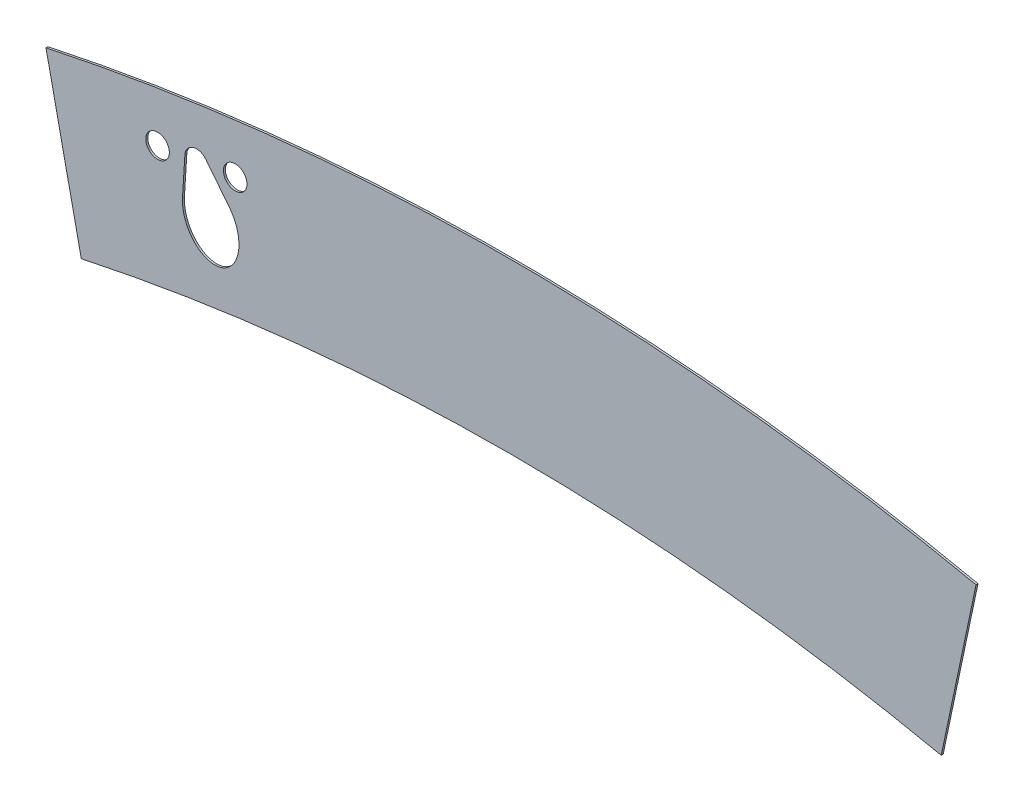
SolidWorks part; units mm, degrees
material "6061 Alloy"
ref_plane "front" through (0, 0, 0) normal (0, 0, 1) x (1, 0, 0)
ref_plane "top" through (0, 0, 0) normal (0, 1, 0) x (1, 0, 0)
ref_plane "right" through (0, 0, 0) normal (1, 0, 0) x (0, 0, -1)
sketch "Sketch1" plane through (0, 0, 0) normal (0, 0, 1) x (1, 0, 0)
  line L0 (0, 0) -> (0, -273.05) construction
  line L1 (0, 0) -> (383.281, 0) construction
  line L2 (-752.475, -79.7743) -> (-695.3504, -346.782)
  line L3 (752.475, -79.7743) -> (696.1124, -346.9455)
  line L4 (-533.4, -39.8611) -> (-450.8253, -303.8415) construction
  line L5 (-527.7688, -117.4654) -> (-531.605, -179.2171)
  line L6 (-493.8044, -106.8411) -> (-455.4626, -155.3993)
  arc A0 (752.475, -79.7743) -> (-752.475, -79.7743) centre (0, -3588.766) ccw
  arc A1 (696.1124, -346.9455) -> (-695.3504, -346.782) centre (0, -3588.766) ccw
  circle A2 centre (-446.3034, -108.204) radius 19.05
  arc A3 (-493.8044, -106.8411) -> (-527.7688, -117.4654) centre (-508.7554, -118.6466) ccw
  circle A4 centre (-571.9318, -126.7714) radius 19.05
  ellipse E0 centre (-486.0066, -191.3716) end of major axis (-503.0682, -136.8278) minor radius 44.45 (-531.605, -179.2171) -> (-455.4626, -155.3993) ccw
  dimension "D1" = 3588.766
  dimension "D5" = 17.37
  dimension "D7" = 38.1
  dimension "D12" = 19.05
  dimension "D2" = 1504.95
  dimension "D3" = 273.05
  dimension "D4" = 695.3504
  dimension "D6" = 533.4
  dimension "D8" = 158.75
  dimension "D9" = 88.9
  dimension "D10" = 57.15
  dimension "D11" = 752.475
  dimension "D13" = 696.1124
  dimension "D14" = 82.55
  dimension "D15" = 446.3034
  dimension "D16" = 108.204
  dimension "D17" = 63.3191
  dimension "D18" = 571.9318
  dimension "D19" = 126.7714
  dimension "D20" = 126.9931
extrude "Base-Extrude" add sketch "Sketch1" against normal blind 3.175
